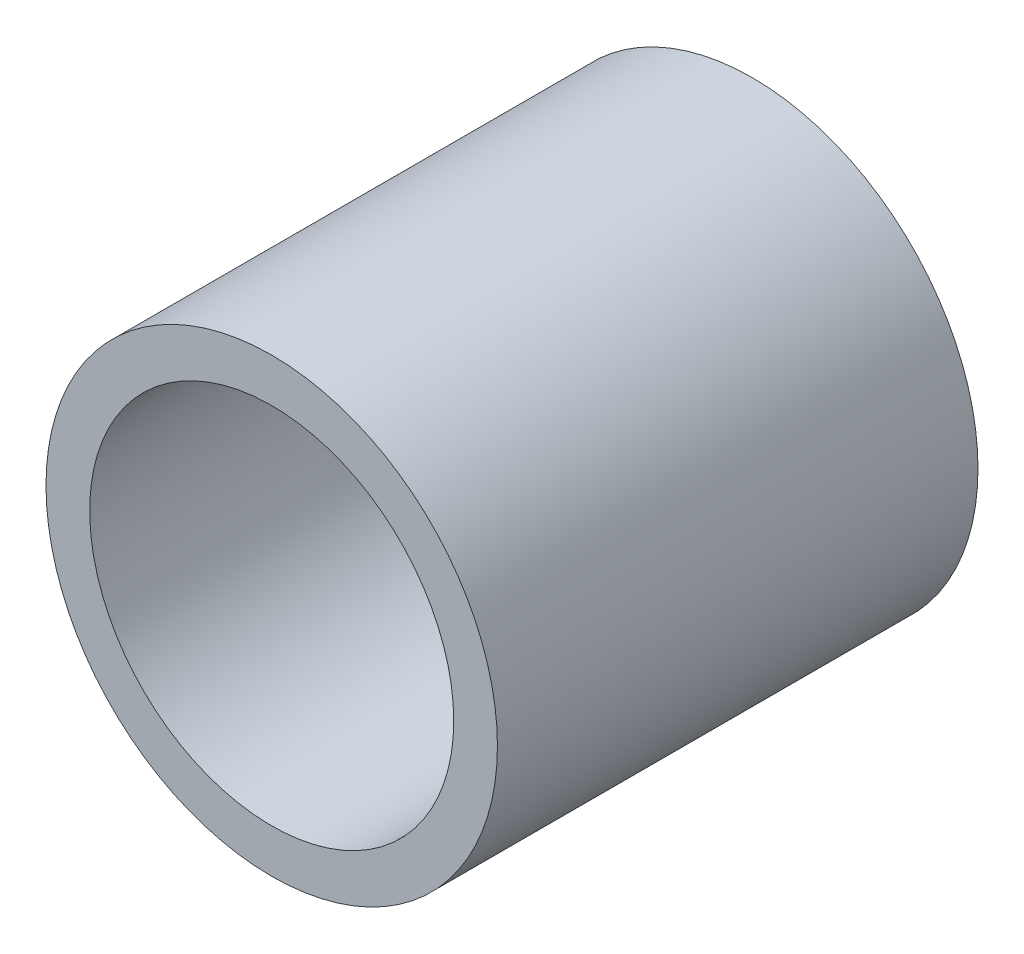
SolidWorks part; units mm, degrees
ref_plane "Front Plane" through (0, 0, 0) normal (0, 0, 1) x (1, 0, 0)
ref_plane "Top Plane" through (0, 0, 0) normal (0, 1, 0) x (1, 0, 0)
ref_plane "Right Plane" through (0, 0, 0) normal (1, 0, 0) x (0, 0, -1)
sketch "Sketch2" plane through (0, 0, 0) normal (0, 0, 1) x (1, 0, 0)
  circle A0 centre (0, 0) radius 12.5
  circle A1 centre (0, 0) radius 15.5
extrude "Boss-Extrude1" add sketch "Sketch2" along normal blind 33
